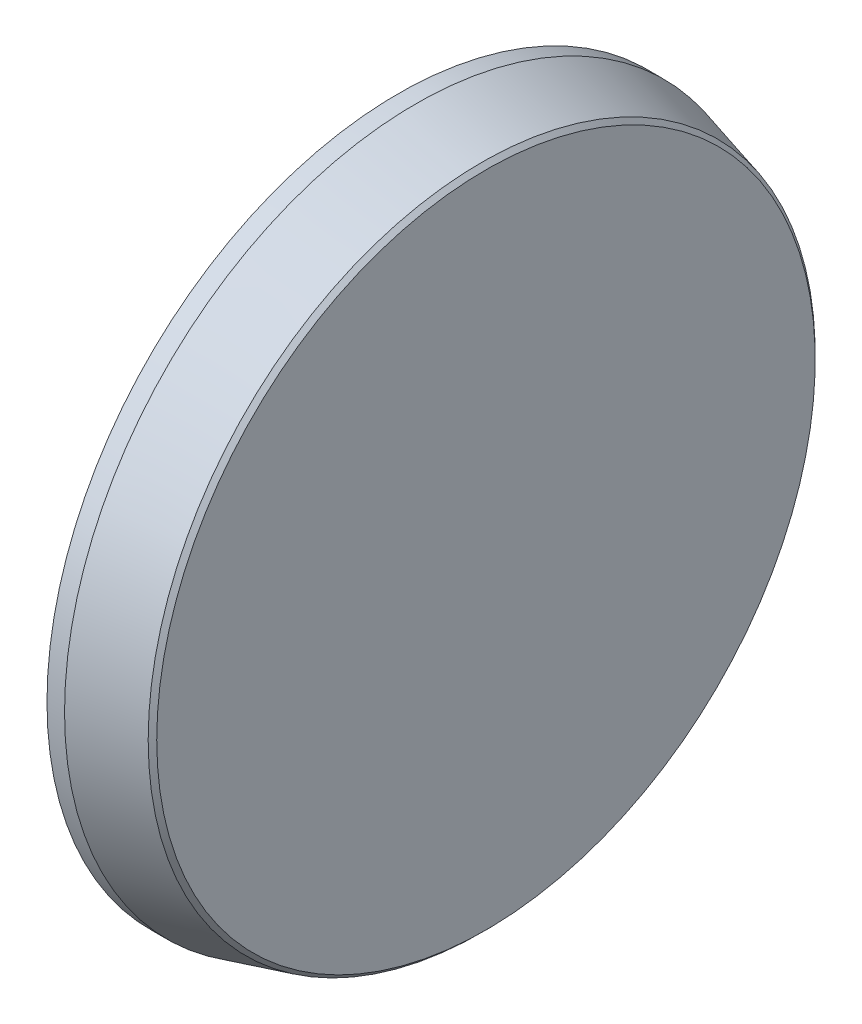
SolidWorks part; units mm, degrees
ref_plane "Спереди" through (0, 0, 0) normal (0, 0, 1) x (1, 0, 0)
ref_plane "Сверху" through (0, 0, 0) normal (0, 1, 0) x (1, 0, 0)
ref_plane "Справа" through (0, 0, 0) normal (1, 0, 0) x (0, 0, -1)
sketch "Эскиз1" plane through (0, 0, 0) normal (0, 0, 1) x (1, 0, 0)
  line L0 (0, 100) -> (0, -100)
  line L1 (0, 100) -> (90, 100)
  line L2 (90, 100) -> (90, 355)
  line L3 (90, 355) -> (20, 355)
  line L4 (20, 355) -> (20, 400)
  line L5 (20, 400) -> (40, 400)
  line L6 (120, 375) -> (120, -375)
  line L7 (0, 0) -> (105.1278, 0) construction
  line L8 (0, -100) -> (90, -100)
  line L14 (40, 400) -> (115.1314, 379.8686)
  line L15 (115.1314, 379.8686) -> (120, 375)
  line L16 (115.1314, -379.8686) -> (120, -375)
  line L17 (40, -400) -> (115.1314, -379.8686)
  line L18 (20, -400) -> (40, -400)
  line L19 (20, -355) -> (20, -400)
  line L20 (90, -355) -> (20, -355)
  line L21 (90, -100) -> (90, -355)
  line L22 (0, 0) -> (120, 0)
  point P14 (120, 0)
  point P15 (85, 0)
  dimension "D1" = 200
  dimension "D4" = 120
  dimension "D5" = 30
  dimension "D2" = 45
  dimension "D3" = 15
  dimension "D6" = 45
  dimension "D7" = 20
  dimension "D8" = 100
  dimension "D9" = 750
  dimension "D10" = 800
revolve "Повернуть7" add sketch "Эскиз1" angle 360 about L7
sketch "Эскиз3" plane through (90, 0, 0) normal (-1, 0, 0) x (0, 0, 1)
  line L0 (20, 105.8301) -> (20, 343.6932)
  line L1 (-20, 105.8301) -> (-20, 283.9454)
  line L2 (88.9753, 60.691) -> (257.1699, 228.8856)
  line L3 (0, 375) -> (0, -375) construction
  line L4 (60.691, 88.9753) -> (186.6376, 214.9219)
  line L5 (105.8301, -20) -> (343.6932, -20)
  line L6 (105.8301, 20) -> (283.9454, 20)
  line L7 (60.691, -88.9753) -> (228.8856, -257.1699)
  line L8 (88.9753, -60.691) -> (214.9219, -186.6376)
  line L9 (-20, -105.8301) -> (-20, -343.6932)
  line L10 (20, -105.8301) -> (20, -283.9454)
  line L11 (-88.9753, -60.691) -> (-257.1699, -228.8856)
  line L12 (-60.691, -88.9753) -> (-186.6376, -214.9219)
  line L13 (-105.8301, 20) -> (-343.6932, 20)
  line L14 (-105.8301, -20) -> (-283.9454, -20)
  line L15 (-60.691, 88.9753) -> (-228.8856, 257.1699)
  line L16 (-88.9753, 60.691) -> (-214.9219, 186.6376)
  circle A0 centre (0, 0) radius 100 construction
  circle A1 centre (0, 0) radius 355 construction
  circle A2 centre (0, 0) radius 355 construction
  arc A3 (-20, 283.9454) -> (-96.2712, 341.697) centre (-80, 283.9454) ccw
  arc A4 (30.8696, 353.6553) -> (20, 343.6932) centre (30, 343.6932) ccw
  arc A5 (-27.2727, 96.2091) -> (-20, 105.8301) centre (-30, 105.8301) ccw
  arc A6 (20, 105.8301) -> (27.2727, 96.2091) centre (30, 105.8301) ccw
  circle A7 centre (0, 0) radius 355
  circle A8 centre (0, 0) radius 100
  circle A9 centre (0, 0) radius 100 construction
  arc A10 (186.6376, 214.9219) -> (173.5423, 309.6903) centre (144.2112, 257.3483) ccw
  arc A11 (48.7454, 87.3149) -> (60.691, 88.9753) centre (53.6199, 96.0464) ccw
  arc A12 (88.9753, 60.691) -> (87.3149, 48.7454) centre (96.0464, 53.6199) ccw
  arc A13 (271.9001, 228.244) -> (257.1699, 228.8856) centre (264.241, 221.8146) ccw
  arc A14 (283.9454, 20) -> (341.697, 96.2712) centre (283.9454, 80) ccw
  arc A15 (96.2091, 27.2727) -> (105.8301, 20) centre (105.8301, 30) ccw
  arc A16 (105.8301, -20) -> (96.2091, -27.2727) centre (105.8301, -30) ccw
  arc A17 (353.6553, -30.8696) -> (343.6932, -20) centre (343.6932, -30) ccw
  arc A18 (214.9219, -186.6376) -> (309.6903, -173.5423) centre (257.3483, -144.2112) ccw
  arc A19 (87.3149, -48.7454) -> (88.9753, -60.691) centre (96.0464, -53.6199) ccw
  arc A20 (60.691, -88.9753) -> (48.7454, -87.3149) centre (53.6199, -96.0464) ccw
  arc A21 (228.244, -271.9001) -> (228.8856, -257.1699) centre (221.8146, -264.241) ccw
  arc A22 (20, -283.9454) -> (96.2712, -341.697) centre (80, -283.9454) ccw
  arc A23 (27.2727, -96.2091) -> (20, -105.8301) centre (30, -105.8301) ccw
  arc A24 (-20, -105.8301) -> (-27.2727, -96.2091) centre (-30, -105.8301) ccw
  arc A25 (-30.8696, -353.6553) -> (-20, -343.6932) centre (-30, -343.6932) ccw
  arc A26 (-186.6376, -214.9219) -> (-173.5423, -309.6903) centre (-144.2112, -257.3483) ccw
  arc A27 (-48.7454, -87.3149) -> (-60.691, -88.9753) centre (-53.6199, -96.0464) ccw
  arc A28 (-88.9753, -60.691) -> (-87.3149, -48.7454) centre (-96.0464, -53.6199) ccw
  arc A29 (-271.9001, -228.244) -> (-257.1699, -228.8856) centre (-264.241, -221.8146) ccw
  arc A30 (-283.9454, -20) -> (-341.697, -96.2712) centre (-283.9454, -80) ccw
  arc A31 (-96.2091, -27.2727) -> (-105.8301, -20) centre (-105.8301, -30) ccw
  arc A32 (-105.8301, 20) -> (-96.2091, 27.2727) centre (-105.8301, 30) ccw
  arc A33 (-353.6553, 30.8696) -> (-343.6932, 20) centre (-343.6932, 30) ccw
  arc A34 (-214.9219, 186.6376) -> (-309.6903, 173.5423) centre (-257.3483, 144.2112) ccw
  arc A35 (-87.3149, 48.7454) -> (-88.9753, 60.691) centre (-96.0464, 53.6199) ccw
  arc A36 (-60.691, 88.9753) -> (-48.7454, 87.3149) centre (-53.6199, 96.0464) ccw
  arc A37 (-228.244, 271.9001) -> (-228.8856, 257.1699) centre (-221.8146, 264.241) ccw
  circle M9 centre (0, 0) radius 355
  circle M10 centre (0, 0) radius 100
  dimension "D3" = 120
  dimension "D4" = 20
  dimension "D5" = 20
  dimension "D6" = 20
  dimension "D1" = 8
  dimension "D2" = 40
extrude "Бобышка-Вытянуть6" add sketch "Эскиз3" along normal offset from surface (60 mm away) 10 contours A29 A7 A26 L12 A27 A8 A28 L11 | A33 A7 A30 L14 A31 A8 A32 L13 | A37 A7 A34 L16 A35 A8 A36 L15 | A6 L0 A4 A3 L1 A5 M9 M10 | A13 A7 A10 L4 A11 A8 A12 L2 | A17 A7 A14 L6 A15 A8 A16 L5 | A21 A7 A18 L8 A19 A8 A20 L7 | A25 A7 A22 L10 A23 A8 A24 L9 up to face at (20, 0, 400)
equation "\"A\" = 100мм"
equation "\"B\"= 800мм"
equation "\"D4@Эскиз1\"=\"A\" + 20"
equation "\"D8@Эскиз1\"=\"A\""
equation "\"D9@Эскиз1\"=\"B\" - 50"
equation "\"D10@Эскиз1\"=\"B\""
